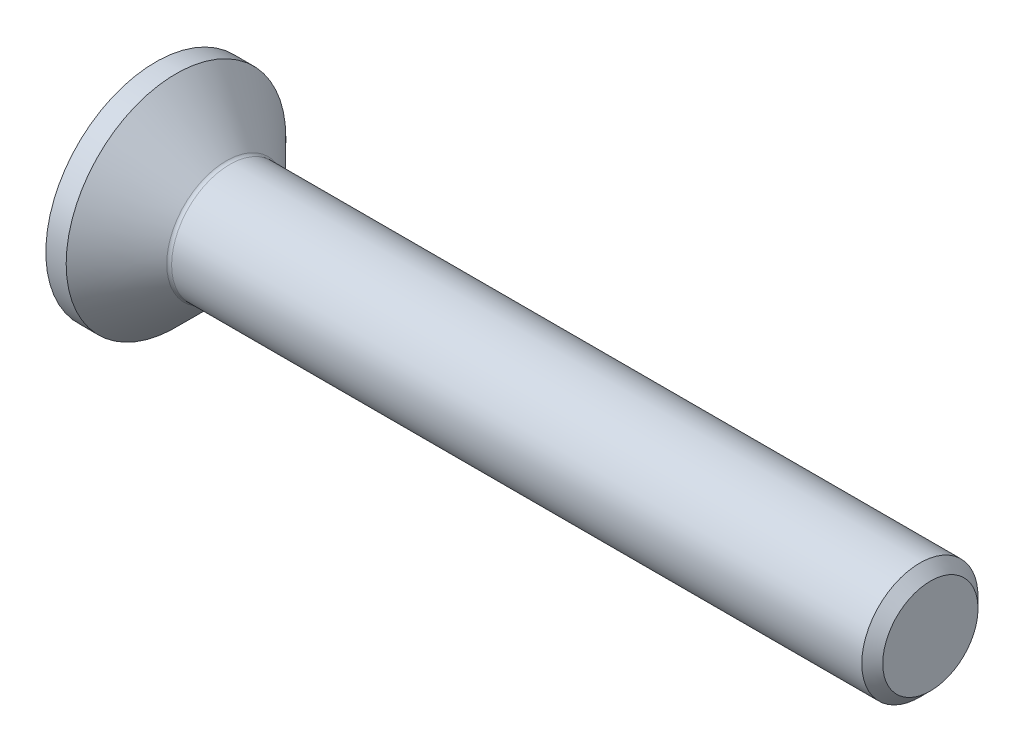
SolidWorks part; units mm, degrees
ref_plane "Front" through (0, 0, 0) normal (0, 0, 1) x (1, 0, 0)
ref_plane "Top" through (0, 0, 0) normal (0, 1, 0) x (1, 0, 0)
ref_plane "Right" through (0, 0, 0) normal (1, 0, 0) x (0, 0, -1)
sketch "Sketch1" plane through (0, 0, 0) normal (0, 0, 1) x (1, 0, 0)
  line L0 (0, 0) -> (0, 6.72)
  line L1 (0, 6.72) -> (3.72, 3)
  line L2 (3.72, 3) -> (40, 3)
  line L3 (40, 3) -> (40, 0)
  line L4 (40, 0) -> (0, 0)
  line L5 (-0.5871, 0) -> (5.4927, 0) construction
  dimension "l" = 40
  dimension "k" = 3.72
  dimension "d" = 6
  dimension "D1" = 45
revolve "Base" add sketch "Sketch1" angle 360 about L5
cosmetic thread "ThreadCosmetic1" parameters "b"=24, "D2"=4.917
sketch "Sketch2" plane through (0, 0, 0) normal (1, 0, 0) x (0, 0, -1)
  line L1 (2.3094, 0) -> (1.1547, 2)
  line L2 (1.1547, 2) -> (-1.1547, 2)
  line L3 (-1.1547, 2) -> (-2.3094, 0)
  line L4 (-2.3094, 0) -> (-1.1547, -2)
  line L5 (-1.1547, -2) -> (1.1547, -2)
  line L6 (1.1547, -2) -> (2.3094, 0)
  circle A0 centre (0, 0) radius 2 construction
  dimension "s" = 4
extrude "HexagonSocket" cut sketch "Sketch2" along normal blind 2.2
sketch "Sketch3" plane through (0, 0, 0) normal (0, 0, 1) x (1, 0, 0)
  line L0 (-0.4391, 0) -> (4.425, 0) construction
  line L1 (2.2, 0) -> (2.2, -2) construction
  line L2 (2.2, 2) -> (3.3547, 0)
  line L3 (3.3547, 0) -> (2.2, -2) construction
  line L4 (2.2, 2) -> (2.2, 0)
  line L5 (2.2, 0) -> (3.3547, 0)
  line L7 (2.2, 2) -> (2.2, 0) construction
  dimension "D1" = 120
revolve "Cut-Revolve1" cut sketch "Sketch3" angle 360 about L0
fillet "HeadFillet" radius 0.25 1 edges at (3.72, 0, 3)
chamfer "Chamfer" distance 0.5415 angle 45 1 edges at (40, 0, 3)
sketch "Sketch4" plane through (0, 0, 0) normal (0, 1, 0) x (1, 0, 0)
  line L0 (11.8531, 0) -> (-2.694, 0) construction
  line L1 (-2, 10.67) -> (3, 10.67)
  line L2 (-2, 10.67) -> (-2, 5.67)
  line L3 (-2, 5.67) -> (3, 5.67)
  line L4 (3, 10.67) -> (3, 5.67)
  line L5 (0, 6.72) -> (0, -6.72) construction
  dimension "dk" = 11.34
  dimension "D2" = 2
  dimension "D3" = 5
  dimension "D4" = 5
revolve "Cut-Revolve2" cut sketch "Sketch4" angle 360 about L0
sketch "Sketch5" plane through (0, 0, 0) normal (0, 0, 1) x (1, 0, 0)
  line L0 (39.4585, 2.531) -> (39.7292, 3)
  line L1 (39.7292, 3) -> (39.7292, 3.5415)
  line L2 (39.7292, 3.5415) -> (39.1877, 3.5415)
  line L3 (39.1877, 3.5415) -> (39.1877, 3)
  line L4 (39.1877, 3) -> (39.4585, 2.531)
  line L5 (0, 0) -> (10.6885, 0) construction
  line L6 (39.4585, 3) -> (39.4585, -3) construction
  dimension "D1" = 6
  dimension "D2" = 0.5415
revolve "Cut-Revolve10" [suppressed] cut sketch "Sketch5" angle 360 about L5
pattern_linear "LPattern10" [suppressed] count 37 spacing 0.6498 along (1, 0, 0)
equation "\"D1@Chamfer\" = (  \"d@Sketch1\" - \"D2@ThreadCosmetic1\" )  / 2"
equation "\"D1@Sketch5\" = \"d@Sketch1\""
equation "\"D2@Sketch5\" =  ( \"d@Sketch1\" - \"D2@ThreadCosmetic1\" )  / 2"
equation "\"D3@LPattern10\" = \"D2@Sketch5\" * 1.2"
equation "\"D1@LPattern10\" = \"b@ThreadCosmetic1\" / \"D3@LPattern10\""
